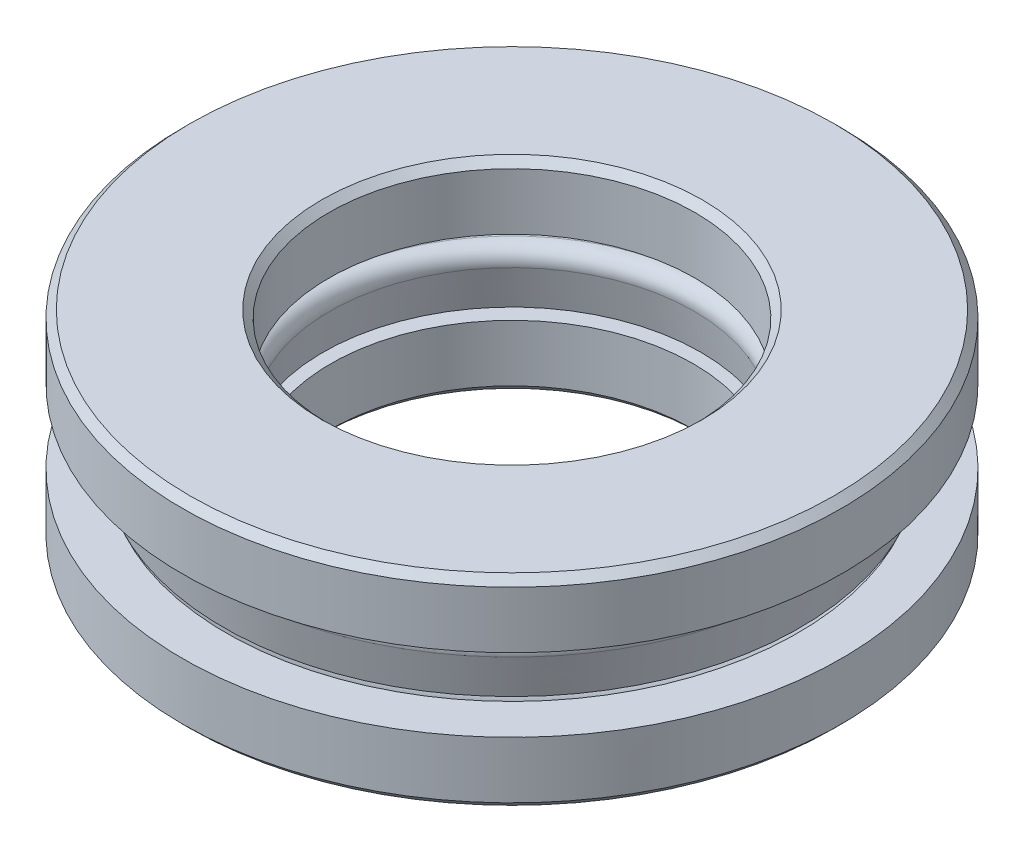
SolidWorks part; units mm, degrees
ref_plane "前视基准面" through (0, 0, 0) normal (0, 0, 1) x (1, 0, 0)
ref_plane "上视基准面" through (0, 0, 0) normal (0, 1, 0) x (1, 0, 0)
ref_plane "右视基准面" through (0, 0, 0) normal (1, 0, 0) x (0, 0, -1)
sketch "草图3" plane through (0, 0, 0) normal (0, 1, 0) x (1, 0, 0)
  line L0 (0, 7.795) -> (0, 5.235)
  circle A0 centre (0, 0) radius 6.515 construction
  arc A1 (0, 5.235) -> (0, 7.795) centre (0, 6.515) ccw
  dimension "D1" = 13.03
  dimension "D2" = 1.28
sketch "草图4" plane through (0, 0, 0) normal (1, 0, 0) x (0, 0, -1)
  line L0 (0, -2.75) -> (0, 2.75) construction
  line L1 (-4.95, -2.75) -> (-4.95, -1)
  line L2 (-5, 2.75) -> (-9, 2.75)
  line L3 (-9, 2.75) -> (-9, 1)
  line L4 (-9, 1) -> (-7.8, 1)
  line L5 (-5, 2.75) -> (-5, 1)
  line L6 (-5, 1) -> (-5.5, 1)
  line L7 (6.515, 0) -> (-6.515, 0) construction
  line L8 (0, 0) -> (-9, 0) construction
  line L9 (-4.95, -2.75) -> (-9, -2.75)
  line L10 (-9, -2.75) -> (-9, -1)
  line L11 (-9, -1) -> (-7.8, -1)
  line L12 (-4.95, -1) -> (-5.5, -1)
  arc A0 (-5.5, 1) -> (-7.8, 1) centre (-6.65, -1.2198) ccw
  arc A1 (-5.5, -1) -> (-7.8, -1) centre (-6.65, 1.2198) cw
  point P3 (-6.65, 1.2802)
  point P4 (0, 0)
  point P42 (-6.65, -1.2802)
  dimension "D1" = 5.5
  dimension "D7" = 2.5
  dimension "D2" = 10
  dimension "D3" = 18
  dimension "D4" = 0.5
  dimension "D5" = 1.2
  dimension "D6" = 1.75
  dimension "D8" = 9.9
revolve "旋转1" add sketch "草图4" angle 360 about L0
revolve "旋转2" add sketch "草图3" angle 360 about L0
pattern_circular "阵列(圆周)2" count 8 over 360 about axis through (0, 0, 0) along (0, 1, 0) of bodies 103
sketch "草图5" plane through (0, 0, 0) normal (1, 0, 0) x (0, 0, -1)
  line L0 (-7.8615, 0.2653) -> (-7.6737, -0.8)
  line L1 (-7.6737, -0.8) -> (-7.8706, -0.8347)
  line L2 (-7.8706, -0.8347) -> (-8.0585, 0.2305)
  line L3 (-7.6646, 0.7) -> (-5.3654, 0.7)
  line L7 (-5.3654, 0.5) -> (-7.6646, 0.5)
  line L8 (-6.515, 0.7) -> (-6.515, 0.5) construction
  line L9 (0, 0) -> (0, 2.75) construction
  line L10 (5, 2.75) -> (-5, 2.75) construction
  line L11 (-5.3563, -0.8) -> (-5.1594, -0.8347)
  line L12 (-5.1685, 0.2653) -> (-5.3563, -0.8)
  line L13 (-5.1594, -0.8347) -> (-4.9715, 0.2305)
  arc A2 (-7.8615, 0.2653) -> (-7.6646, 0.5) centre (-7.6646, 0.3) cw
  arc A4 (-8.0585, 0.2305) -> (-7.6646, 0.7) centre (-7.6646, 0.3) cw
  arc A5 (-5.1685, 0.2653) -> (-5.3654, 0.5) centre (-5.3654, 0.3) ccw
  arc A6 (-4.9715, 0.2305) -> (-5.3654, 0.7) centre (-5.3654, 0.3) ccw
  circle A9 centre (-6.515, 0) radius 1.28
  circle A10 centre (-6.515, 0) radius 1.28 construction
  dimension "D7" = 0.2
  dimension "D8" = 0.8
  dimension "D5" = 0.4
  dimension "D1" = 0.2
  dimension "D2" = 0.2
  dimension "D4" = 0.5
  dimension "D6" = 80
  dimension "D9" = 0
revolve "旋转5" add sketch "草图5" angle 360 about L9
chamfer "倒角1" distance 0.2 angle 45 2 edges at (0, 2.75, -9) (0, 2.75, -5)
chamfer "倒角2" distance 0.2 angle 45 2 edges at (0, -2.75, -9) (0, -2.75, -4.95)
